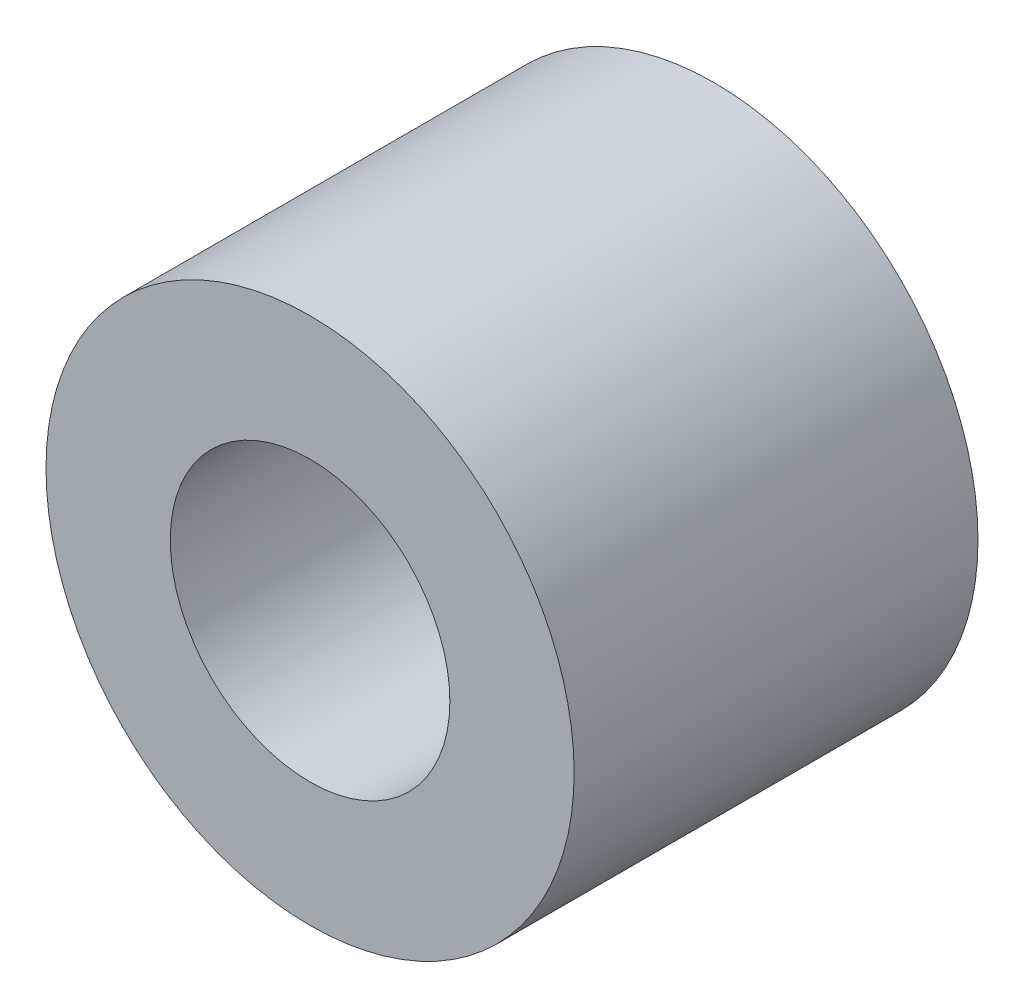
SolidWorks part; units mm, degrees
material "Borracha"
ref_plane "Plano frontal" through (0, 0, 0) normal (0, 0, 1) x (1, 0, 0)
ref_plane "Plano superior" through (0, 0, 0) normal (0, 1, 0) x (1, 0, 0)
ref_plane "Plano direito" through (0, 0, 0) normal (1, 0, 0) x (0, 0, -1)
sketch "Esboço2" plane through (0, 0, 0) normal (0, 0, 1) x (1, 0, 0)
  circle A0 centre (0, 0) radius 8.5
  dimension "D1" = 17
extrude "Ressalto-extrusão1" add sketch "Esboço2" along normal blind 13
sketch "Esboço3" plane through (0, 0, 13) normal (0, 0, 1) x (1, 0, 0)
  circle A0 centre (0, 0) radius 4.5
  dimension "D1" = 9
extrude "Corte-extrusão1" cut sketch "Esboço3" against normal blind 16
